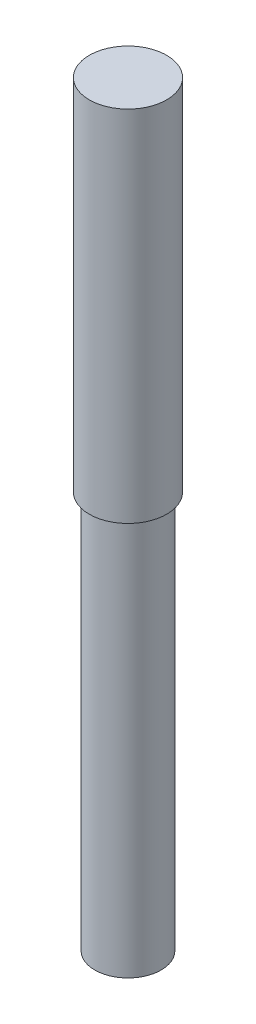
SolidWorks part; units mm, degrees
ref_plane "Front Plane" through (0, 0, 0) normal (0, 0, 1) x (1, 0, 0)
ref_plane "Top Plane" through (0, 0, 0) normal (0, 1, 0) x (1, 0, 0)
ref_plane "Right Plane" through (0, 0, 0) normal (1, 0, 0) x (0, 0, -1)
sketch "Sketch1" plane through (0, 0, 0) normal (0, 1, 0) x (1, 0, 0)
  circle A0 centre (0, 0) radius 6
extrude "Boss-Extrude1" add sketch "Sketch1" along normal blind 72
sketch "Sketch2" plane through (0, 72, 0) normal (0, 1, 0) x (1, 0, 0)
  circle A0 centre (0, 0) radius 7
extrude "Boss-Extrude2" add sketch "Sketch2" along normal blind 65
